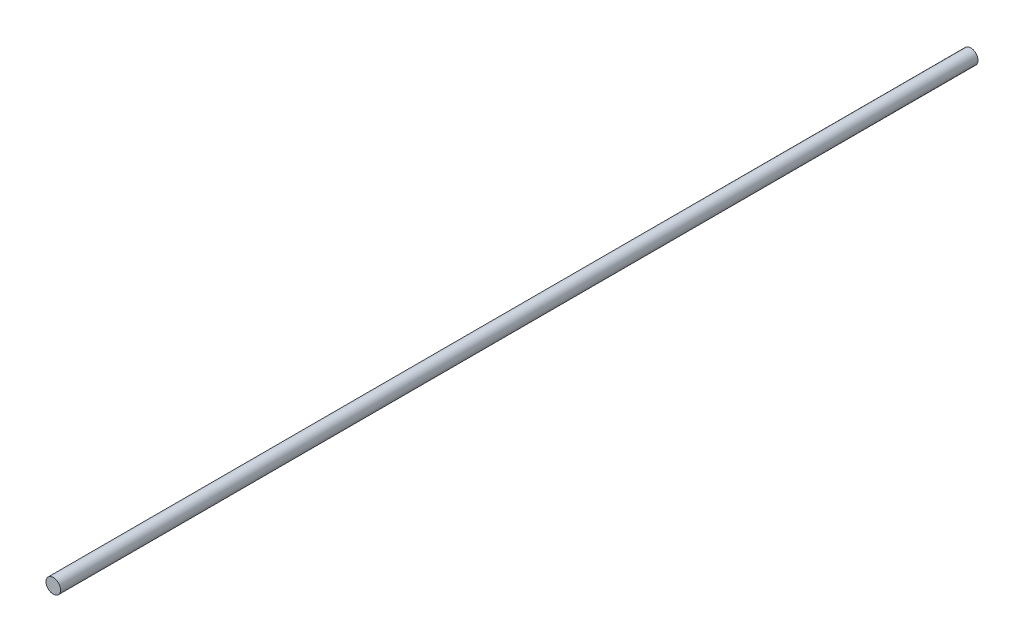
SolidWorks part; units mm, degrees
material "Hexcel AS4C (3000 filamentos)"
ref_plane "Alzado" through (0, 0, 0) normal (0, 0, 1) x (1, 0, 0)
ref_plane "Planta" through (0, 0, 0) normal (0, 1, 0) x (1, 0, 0)
ref_plane "Vista lateral" through (0, 0, 0) normal (1, 0, 0) x (0, 0, -1)
sketch "Croquis1" plane through (0, 0, 0) normal (0, 0, 1) x (1, 0, 0)
  circle A0 centre (0, 0) radius 3.175
  dimension "D1" = 6.35
extrude "Saliente-Extruir1" add sketch "Croquis1" along normal blind 400
